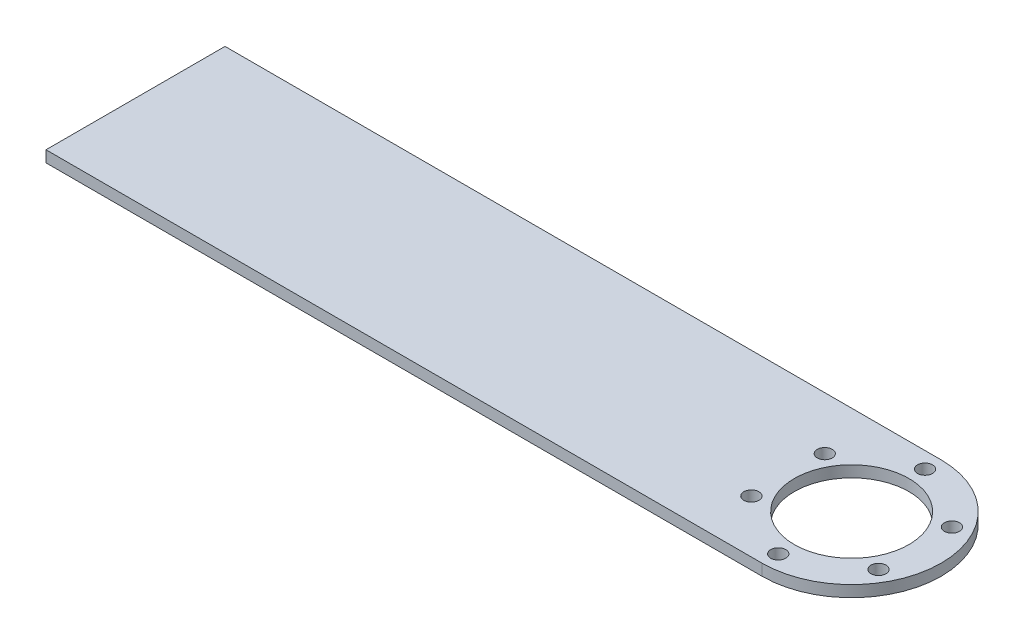
SolidWorks part; units mm, degrees
material "ASTM A36 Steel"
ref_plane "Alzado" through (0, 0, 0) normal (0, 0, 1) x (1, 0, 0)
ref_plane "Planta" through (0, 0, 0) normal (0, 1, 0) x (1, 0, 0)
ref_plane "Vista lateral" through (0, 0, 0) normal (1, 0, 0) x (0, 0, -1)
sketch "Sketch1" plane through (0, 0, 0) normal (0, 1, 0) x (1, 0, 0)
  line L1 (-100, -25) -> (100, -25)
  line L2 (-100, -25) -> (-100, 25)
  line L3 (-100, 25) -> (100, 25)
  line L5 (-100, -25) -> (100, 25) construction
  line L6 (-100, 25) -> (100, -25) construction
  arc A0 (100, -25) -> (100, 25) centre (100, 0) ccw
  point P0 (0, 0)
  point P6 (112.968, 0)
  point P8 (102.1262, 0)
  point P9 (0, 0)
  dimension "D2" = 200
  dimension "D1" = 50
extrude "Boss-Extrude1" add sketch "Sketch1" along normal blind 3.175
sketch "Sketch2" plane through (0, 3.175, 0) normal (0, 1, 0) x (1, 0, 0)
  line L0 (116, 0) -> (125, 0) construction
  circle A0 centre (100, 0) radius 16
  circle A1 centre (100, 0) radius 20.5 construction
  arc A2 (100, -25) -> (100, 25) centre (100, 0) ccw construction
  circle A3 centre (100, 20.5) radius 2.1
  circle A4 centre (117.7535, 10.25) radius 2.1
  circle A5 centre (117.7535, -10.25) radius 2.1
  circle A6 centre (100, -20.5) radius 2.1
  circle A7 centre (82.2465, -10.25) radius 2.1
  circle A8 centre (82.2465, 10.25) radius 2.1
  point P9 (120.5, 0)
  point P12 (100, 0)
  point P24 (100, 0)
  dimension "D1" = 32
  dimension "D2" = 4.2
  dimension "D3" = 6
extrude "Cut-Extrude1" cut sketch "Sketch2" against normal through all
